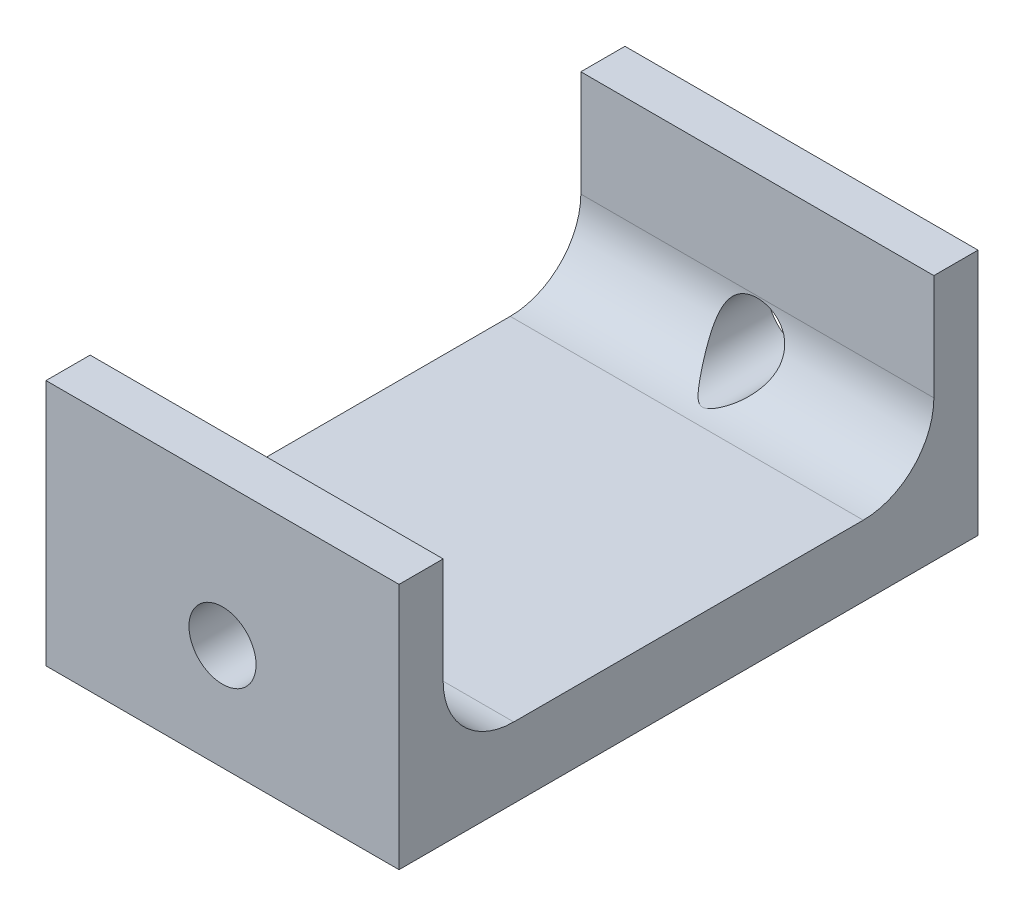
SolidWorks part; units mm, degrees
ref_plane "Alzado" through (0, 0, 0) normal (0, 0, 1) x (1, 0, 0)
ref_plane "Planta" through (0, 0, 0) normal (0, 1, 0) x (1, 0, 0)
ref_plane "Vista lateral" through (0, 0, 0) normal (1, 0, 0) x (0, 0, -1)
sketch "Croquis1" plane through (0, 0, 0) normal (0, 0, 1) x (1, 0, 0)
  line L0 (-10, -1) -> (10, -1) construction
  line L1 (-10, 7) -> (10, 7)
  line L2 (-10, 7) -> (-10, -7)
  line L3 (-10, -7) -> (10, -7)
  line L4 (10, 7) -> (10, -7)
  line L5 (-10, 7) -> (10, -7) construction
  line L6 (-10, -7) -> (10, 7) construction
  point P0 (0, 0)
  dimension "D1" = 20
  dimension "D2" = 6
  dimension "D3" = 14
extrude "Saliente-Extruir1" add sketch "Croquis1" along normal blind 32.8
sketch "Croquis2" plane through (0, 7, 0) normal (0, 1, 0) x (1, 0, 0)
  line L0 (-10, -32.8) -> (-10, 0) construction
  line L1 (-10, -2.5) -> (10, -2.5)
  line L2 (-10, -2.5) -> (-10, -30.3)
  line L3 (-10, -30.3) -> (10, -30.3)
  line L4 (10, -2.5) -> (10, -30.3)
  line L5 (10, -32.8) -> (10, 0) construction
  line L6 (10, -32.8) -> (-10, -32.8) construction
  line L7 (10, 0) -> (-10, 0) construction
  dimension "D1" = 2.5
  dimension "D2" = 2.5
extrude "Cortar-Extruir2" cut sketch "Croquis2" against normal blind 10
fillet "Redondeo1" radius 4 2 edges at (0, -3, 30.3) (0, -3, 2.5)
sketch "Croquis3" plane through (0, 0, 0) normal (0, 0, -1) x (-1, 0, 0)
  line L0 (-10, -1) -> (10, -1) construction
  line L1 (-10, -7) -> (-10, 7) construction
  line L2 (10, 7) -> (10, -7) construction
  line L3 (0, 7) -> (0, -7) construction
  line L4 (-10, 7) -> (10, 7) construction
  line L5 (10, -7) -> (-10, -7) construction
  circle A0 centre (0, -1) radius 1.9
  dimension "D2" = 3.8
  dimension "D1" = 6
extrude "Cortar-Extruir3" cut sketch "Croquis3" against normal blind 36
sketch "Croquis4" plane through (0, -3, 0) normal (0, 1, 0) x (1, 0, 0)
  line L0 (0, 0) -> (0, -32.8) construction
  line L1 (10, -32.8) -> (-10, -32.8) construction
  line L2 (-10, -16.4) -> (10, -16.4) construction
  line L3 (-10, -6.5) -> (-10, -26.3) construction
  line L4 (10, -26.3) -> (10, -6.5) construction
